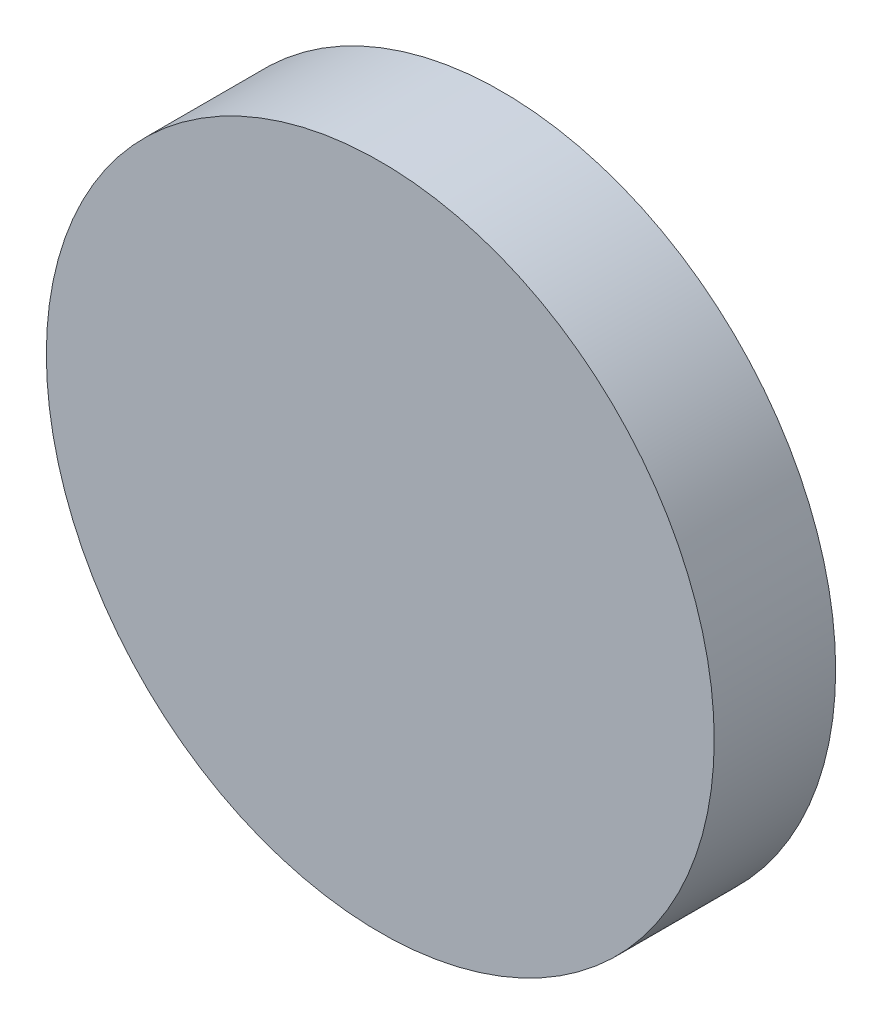
SolidWorks part; units mm, degrees
ref_plane "Front Plane" through (0, 0, 0) normal (0, 0, 1) x (1, 0, 0)
ref_plane "Top Plane" through (0, 0, 0) normal (0, 1, 0) x (1, 0, 0)
ref_plane "Right Plane" through (0, 0, 0) normal (1, 0, 0) x (0, 0, -1)
sketch "Sketch1" plane through (0, 0, 0) normal (0, 0, 1) x (1, 0, 0)
  circle A0 centre (0, 0) radius 5500
  dimension "D1" = 11000
extrude "Boss-Extrude1" add sketch "Sketch1" along normal mid plane 2000
